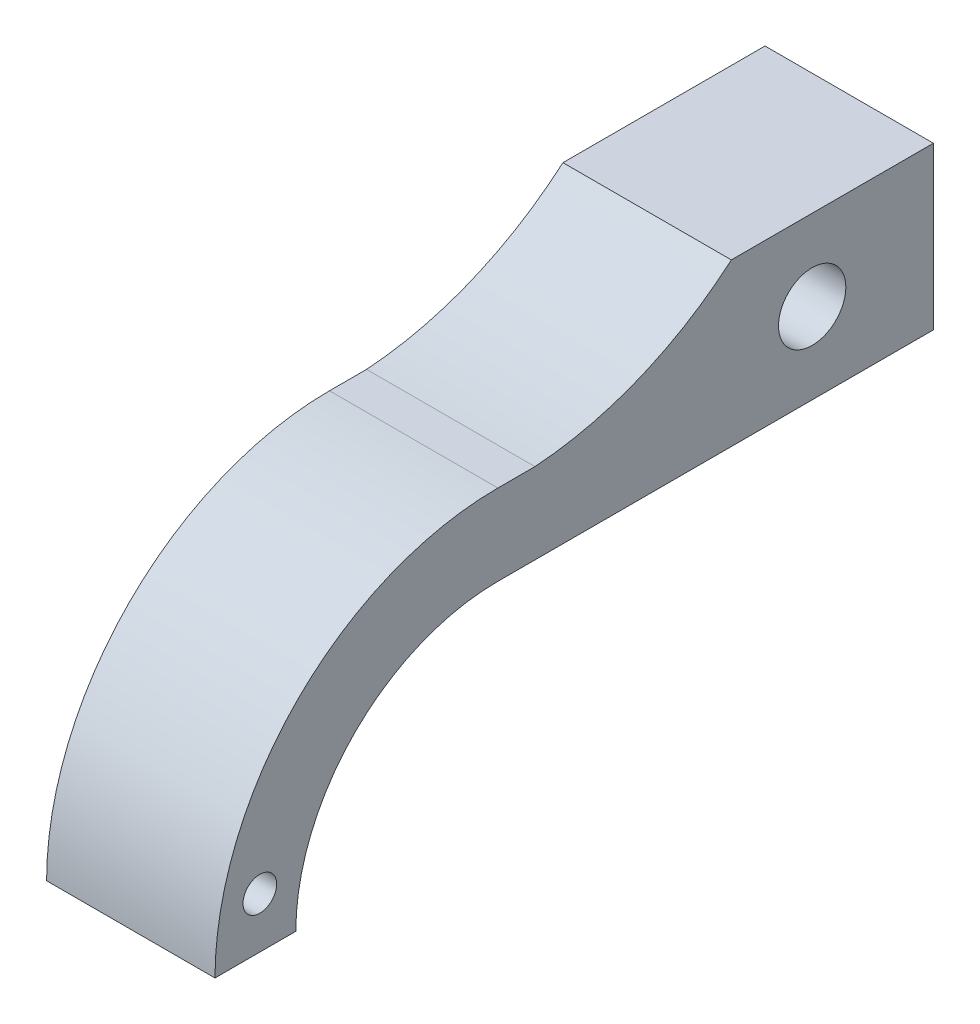
SolidWorks part; units mm, degrees
ref_plane "Front Plane" through (0, 0, 0) normal (0, 0, 1) x (1, 0, 0)
ref_plane "Top Plane" through (0, 0, 0) normal (0, 1, 0) x (1, 0, 0)
ref_plane "Right Plane" through (0, 0, 0) normal (1, 0, 0) x (0, 0, -1)
sketch "Sketch2" plane through (0, 0, 0) normal (1, 0, 0) x (0, 0, -1)
  line L1 (-32.4962, -2.9257) -> (-38, -2.9257)
  line L2 (-38, -2.9257) -> (-38, -44.9257) construction
  line L7 (26.6572, -14.9257) -> (-22.6882, -14.9257)
  line L8 (26.6572, -14.9257) -> (26.6572, 9.0743)
  line L9 (26.6572, 9.0743) -> (-3.3428, 9.0743)
  line L11 (26.6572, -14.9257) -> (-3.3428, 9.0743) construction
  line L12 (26.6572, 9.0743) -> (-22.6882, -14.9257) construction
  line L13 (-38, -44.9257) -> (-80, -44.9257) construction
  line L14 (-22.6882, -14.9257) -> (-38, -14.9257)
  line L15 (-80, -44.9257) -> (-68, -44.9257)
  arc A0 (-32.4962, -2.9257) -> (-3.3428, 9.0743) centre (-35.9806, 46.9527) ccw
  arc A1 (-38, -2.9257) -> (-80, -44.9257) centre (-38, -44.9257) ccw
  arc A2 (-38, -14.9257) -> (-68, -44.9257) centre (-38, -44.9257) ccw
  point P0 (0, -11.9137)
  point P5 (8, 0)
  dimension "D3" = 100
  dimension "D6" = 12
  dimension "D1" = 30
  dimension "D2" = 24
  dimension "D4" = 8
  dimension "D5" = 42
extrude "Boss-Extrude6" add sketch "Sketch2" along normal blind 25
ref_plane "Plane1" through (-20, 0, 0) normal (1, 0, 0) x (0, 0, -1)
sketch "Sketch3" plane through (25, 0, 0) normal (1, 0, 0) x (0, 0, -1)
  line L0 (26.6572, 9.0743) -> (-3.3428, 9.0743) construction
  line L1 (26.6572, -14.9257) -> (26.6572, 9.0743) construction
  circle A0 centre (8.6572, -2.9257) radius 5
  dimension "D1" = 10
  dimension "D2" = 12
  dimension "D3" = 18
extrude "Cut-Extrude1" cut sketch "Sketch3" against normal through all
sketch "Sketch4" plane through (25, 0, 0) normal (1, 0, 0) x (0, 0, -1)
  line L0 (-80, -44.9257) -> (-68, -44.9257) construction
  line L1 (26.6572, -14.9257) -> (26.6572, 9.0743) construction
  circle A0 centre (-73.3428, -37.4257) radius 2.5
  dimension "D1" = 5
  dimension "D2" = 7.5
  dimension "D3" = 100
extrude "Cut-Extrude2" cut sketch "Sketch4" against normal through all
